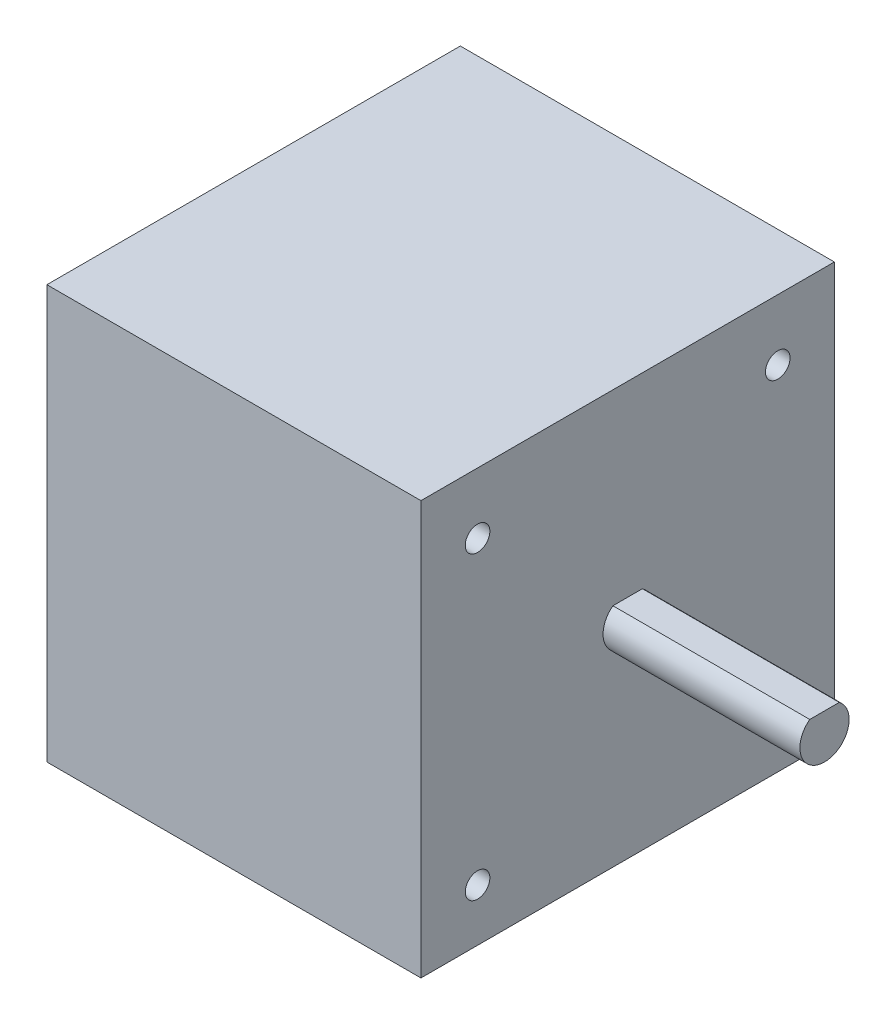
SolidWorks part; units mm, degrees
ref_plane "Front Plane" through (0, 0, 0) normal (0, 0, 1) x (1, 0, 0)
ref_plane "Top Plane" through (0, 0, 0) normal (0, 1, 0) x (1, 0, 0)
ref_plane "Right Plane" through (0, 0, 0) normal (1, 0, 0) x (0, 0, -1)
sketch "草图1" plane through (0, 0, 0) normal (1, 0, 0) x (0, 0, -1)
  line L1 (-21, 21) -> (21, 21)
  line L2 (-21, 21) -> (-21, -21)
  line L3 (-21, -21) -> (21, -21)
  line L4 (21, 21) -> (21, -21)
  line L5 (-21, 21) -> (21, -21) construction
  line L6 (-21, -21) -> (21, 21) construction
  point P0 (0, 0)
  dimension "D1" = 42
extrude "凸台-拉伸1" add sketch "草图1" along normal blind 38
sketch "草图2" plane through (38, 0, 0) normal (1, 0, 0) x (0, 0, -1)
  line L0 (-1.5, 2) -> (1.5, 2)
  line L1 (0, -2.5) -> (6.8004, -2.5) construction
  arc A0 (-1.5, 2) -> (1.5, 2) centre (0, 0) ccw
  dimension "D2" = 5
  dimension "D1" = 4.5
extrude "凸台-拉伸2" add sketch "草图2" along normal blind 20
sketch "草图3" plane through (38, 0, 0) normal (1, 0, 0) x (0, 0, -1)
  line L0 (0, 0) -> (-14.1089, 0) construction
  line L1 (0, 0) -> (0, 12.9755) construction
  circle A1 centre (-15.25, 14.8124) radius 1.25
  circle A2 centre (15.25, 14.8124) radius 1.25
  circle A3 centre (15.4768, -15.6876) radius 1.25
  circle A4 centre (-15.25, -15.6876) radius 1.25
  dimension "D1" = 2.5
  dimension "D2" = 15.25
  dimension "D3" = 15.25
  dimension "D4" = 30.5
extrude "切除-拉伸1" cut sketch "草图3" against normal blind 20
